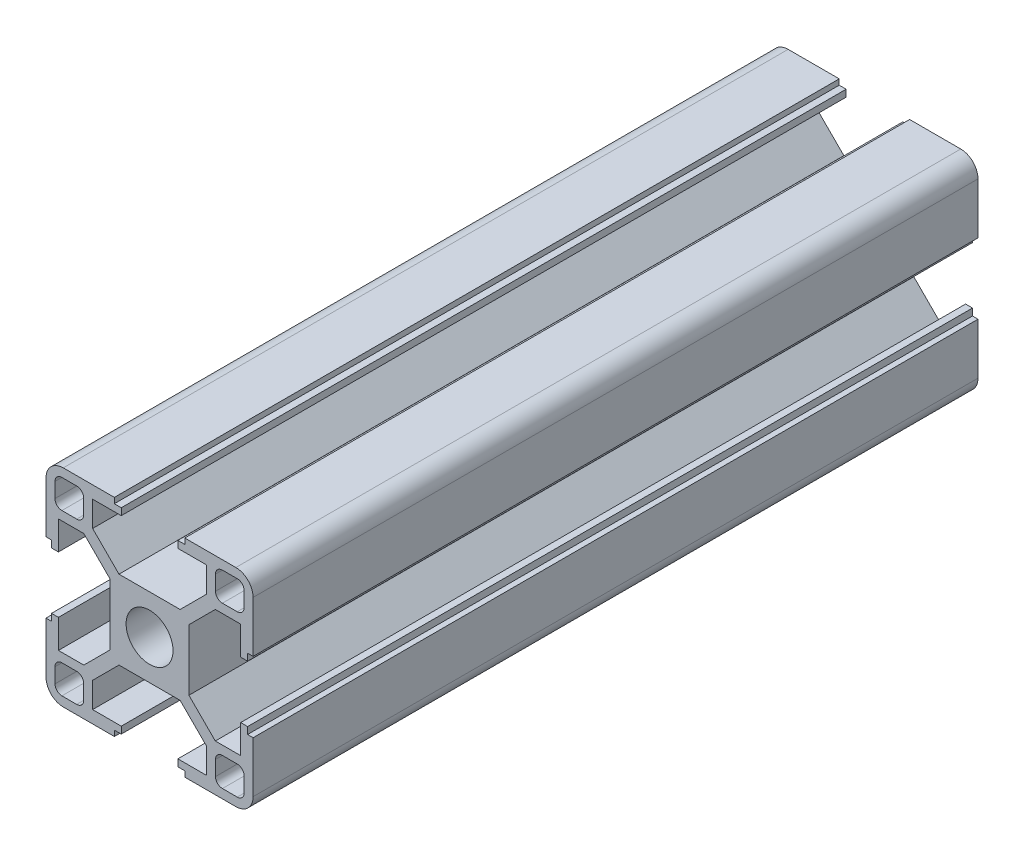
SolidWorks part; units mm, degrees
material "6061-T6 (SS)"
ref_plane "前视基准面" through (0, 0, 0) normal (0, 0, 1) x (1, 0, 0)
ref_plane "上视基准面" through (0, 0, 0) normal (0, 1, 0) x (1, 0, 0)
ref_plane "右视基准面" through (0, 0, 0) normal (1, 0, 0) x (0, 0, -1)
sketch "Sketch1" plane through (0, 0, 0) normal (0, 0, 1) x (1, 0, 0)
  line L0 (-5.1, 15) -> (-5.1, 14.2)
  line L1 (-12.5, -15) -> (12.5, -15)
  line L2 (-15, -12.5) -> (-15, 12.5)
  line L3 (-12.5, 15) -> (12.5, 15)
  line L4 (15, -12.5) -> (15, 12.5)
  line L5 (-15, -15) -> (15, 15) construction
  line L6 (-15, 15) -> (15, -15) construction
  line L7 (-5.1, 14.2) -> (-4.1, 14.2)
  line L8 (-4.1, 14.2) -> (-4.1, 13.2)
  line L9 (-4.1, 13.2) -> (-8.25, 13.2)
  line L10 (-8.25, 13.2) -> (-8.25, 9.5228)
  line L11 (-8.25, 9.5228) -> (-4.4272, 5.7)
  line L12 (-4.4272, 5.7) -> (4.4272, 5.7)
  line L13 (-5.1, 15) -> (5.1, 15)
  line L14 (0, 15) -> (0, 5.7) construction
  line L15 (8.25, 9.5228) -> (4.4272, 5.7)
  line L16 (8.25, 13.2) -> (8.25, 9.5228)
  line L17 (4.1, 13.2) -> (8.25, 13.2)
  line L18 (4.1, 14.2) -> (4.1, 13.2)
  line L19 (5.1, 14.2) -> (4.1, 14.2)
  line L20 (5.1, 15) -> (5.1, 14.2)
  line L21 (15, 5.1) -> (14.2, 5.1)
  line L22 (14.2, 5.1) -> (14.2, 4.1)
  line L23 (14.2, 4.1) -> (13.2, 4.1)
  line L24 (13.2, 4.1) -> (13.2, 8.25)
  line L25 (13.2, 8.25) -> (9.5228, 8.25)
  line L26 (9.5228, 8.25) -> (5.7, 4.4272)
  line L27 (5.7, 4.4272) -> (5.7, -4.4272)
  line L28 (15, 5.1) -> (15, -5.1)
  line L29 (9.5228, -8.25) -> (5.7, -4.4272)
  line L30 (13.2, -8.25) -> (9.5228, -8.25)
  line L31 (13.2, -4.1) -> (13.2, -8.25)
  line L32 (14.2, -4.1) -> (13.2, -4.1)
  line L33 (14.2, -5.1) -> (14.2, -4.1)
  line L34 (15, -5.1) -> (14.2, -5.1)
  line L35 (15, 0) -> (5.7, 0) construction
  line L36 (5.1, -15) -> (5.1, -14.2)
  line L37 (5.1, -14.2) -> (4.1, -14.2)
  line L38 (4.1, -14.2) -> (4.1, -13.2)
  line L39 (4.1, -13.2) -> (8.25, -13.2)
  line L40 (8.25, -13.2) -> (8.25, -9.5228)
  line L41 (8.25, -9.5228) -> (4.4272, -5.7)
  line L42 (4.4272, -5.7) -> (-4.4272, -5.7)
  line L43 (5.1, -15) -> (-5.1, -15)
  line L44 (-8.25, -9.5228) -> (-4.4272, -5.7)
  line L45 (-8.25, -13.2) -> (-8.25, -9.5228)
  line L46 (-4.1, -13.2) -> (-8.25, -13.2)
  line L47 (-4.1, -14.2) -> (-4.1, -13.2)
  line L48 (-5.1, -14.2) -> (-4.1, -14.2)
  line L49 (-5.1, -15) -> (-5.1, -14.2)
  line L50 (0, -15) -> (0, -5.7) construction
  line L51 (-15, -5.1) -> (-14.2, -5.1)
  line L52 (-14.2, -5.1) -> (-14.2, -4.1)
  line L53 (-14.2, -4.1) -> (-13.2, -4.1)
  line L54 (-13.2, -4.1) -> (-13.2, -8.25)
  line L55 (-13.2, -8.25) -> (-9.5228, -8.25)
  line L56 (-9.5228, -8.25) -> (-5.7, -4.4272)
  line L57 (-5.7, -4.4272) -> (-5.7, 4.4272)
  line L58 (-15, -5.1) -> (-15, 5.1)
  line L59 (-9.5228, 8.25) -> (-5.7, 4.4272)
  line L60 (-13.2, 8.25) -> (-9.5228, 8.25)
  line L61 (-13.2, 4.1) -> (-13.2, 8.25)
  line L62 (-14.2, 4.1) -> (-13.2, 4.1)
  line L63 (-14.2, 5.1) -> (-14.2, 4.1)
  line L64 (-15, 5.1) -> (-14.2, 5.1)
  line L65 (-15, 0) -> (-5.7, 0) construction
  line L66 (0, 0) -> (0, 5.7) construction
  circle A0 centre (0, 0) radius 3.4
  arc A1 (-12.5, -15) -> (-15, -12.5) centre (-12.5, -12.5) cw
  arc A2 (12.5, -15) -> (15, -12.5) centre (12.5, -12.5) ccw
  arc A3 (12.5, 15) -> (15, 12.5) centre (12.5, 12.5) cw
  arc A4 (-15, 12.5) -> (-12.5, 15) centre (-12.5, 12.5) cw
  point P0 (0, 0)
  dimension "D3" = 6.8
  dimension "D12" = 2.5
  dimension "D1" = 30
  dimension "D2" = 30
  dimension "D4" = 16.5
  dimension "D5" = 8.2
  dimension "D6" = 10.2
  dimension "D7" = 7.5
  dimension "D9" = 1.8
  dimension "D10" = 1.8
  dimension "D11" = 0.8
  dimension "D8" = 4
extrude "Extrude1" add sketch "Sketch1" along normal blind 105 contours A4 L2 L64 L63 L62 L61 L60 L59 L57 L56 L55 L54 L53 L52 L51 A1 L1 L49 L48 L47 L46 L45 L44 L42 L41 L40 L39 L38 L37 L36 A2 L4 L34 L33 L32 L31 L30 L29 L27 L26 L25 L24 L23 L22 L21 A3 L3 L20
sketch "Sketch2" plane through (0, 0, 105) normal (0, 0, 1) x (1, 0, 0)
  line L0 (13.7, 12.7) -> (13.7, 10.55)
  line L1 (-12.7, 13.7) -> (-10.55, 13.7)
  line L2 (-13.7, 12.7) -> (-13.7, 10.55)
  line L3 (-12.7, 9.55) -> (-10.55, 9.55)
  line L4 (-9.55, 12.7) -> (-9.55, 10.55)
  line L5 (-13.7, 13.7) -> (-9.55, 9.55) construction
  line L6 (-13.7, 9.55) -> (-9.55, 13.7) construction
  line L7 (12.7, 13.7) -> (10.55, 13.7)
  line L8 (9.55, 12.7) -> (9.55, 10.55)
  line L9 (12.7, 9.55) -> (10.55, 9.55)
  line L10 (12.7, -13.7) -> (10.55, -13.7)
  line L11 (13.7, -12.7) -> (13.7, -10.55)
  line L12 (12.7, -9.55) -> (10.55, -9.55)
  line L13 (9.55, -12.7) -> (9.55, -10.55)
  line L14 (-13.7, -12.7) -> (-13.7, -10.55)
  line L15 (-12.7, -13.7) -> (-10.55, -13.7)
  line L16 (-9.55, -12.7) -> (-9.55, -10.55)
  line L17 (-12.7, -9.55) -> (-10.55, -9.55)
  line L18 (0, 0) -> (-9.55, 9.55) construction
  line L19 (-12.5, 15) -> (-5.1, 15) construction
  line L20 (-15, 5.1) -> (-15, 12.5) construction
  line L21 (-13.2, 8.25) -> (-9.5228, 8.25) construction
  line L22 (-8.25, 13.2) -> (-8.25, 9.5228) construction
  arc A0 (-13.7, -12.7) -> (-12.7, -13.7) centre (-12.7, -12.7) ccw
  arc A1 (-10.55, -13.7) -> (-9.55, -12.7) centre (-10.55, -12.7) ccw
  arc A2 (-9.55, -10.55) -> (-10.55, -9.55) centre (-10.55, -10.55) ccw
  arc A3 (-13.7, -10.55) -> (-12.7, -9.55) centre (-12.7, -10.55) cw
  arc A4 (13.7, -10.55) -> (12.7, -9.55) centre (12.7, -10.55) ccw
  arc A5 (12.7, -13.7) -> (13.7, -12.7) centre (12.7, -12.7) ccw
  arc A6 (10.55, -13.7) -> (9.55, -12.7) centre (10.55, -12.7) cw
  arc A7 (10.55, -9.55) -> (9.55, -10.55) centre (10.55, -10.55) ccw
  arc A8 (13.7, 12.7) -> (12.7, 13.7) centre (12.7, 12.7) ccw
  arc A9 (13.7, 10.55) -> (12.7, 9.55) centre (12.7, 10.55) cw
  arc A10 (9.55, 10.55) -> (10.55, 9.55) centre (10.55, 10.55) ccw
  arc A11 (10.55, 13.7) -> (9.55, 12.7) centre (10.55, 12.7) ccw
  arc A12 (-10.55, 13.7) -> (-9.55, 12.7) centre (-10.55, 12.7) cw
  arc A13 (-10.55, 9.55) -> (-9.55, 10.55) centre (-10.55, 10.55) ccw
  arc A14 (-13.7, 10.55) -> (-12.7, 9.55) centre (-12.7, 10.55) ccw
  arc A15 (-12.7, 13.7) -> (-13.7, 12.7) centre (-12.7, 12.7) ccw
  point P0 (-11.625, 11.625)
  dimension "D2" = 1
  dimension "D3" = 1.3
  dimension "D4" = 1.3
  dimension "D5" = 1.3
  dimension "D6" = 1.3
  dimension "D1" = 4
extrude "Extrude2" cut sketch "Sketch2" against normal through all
